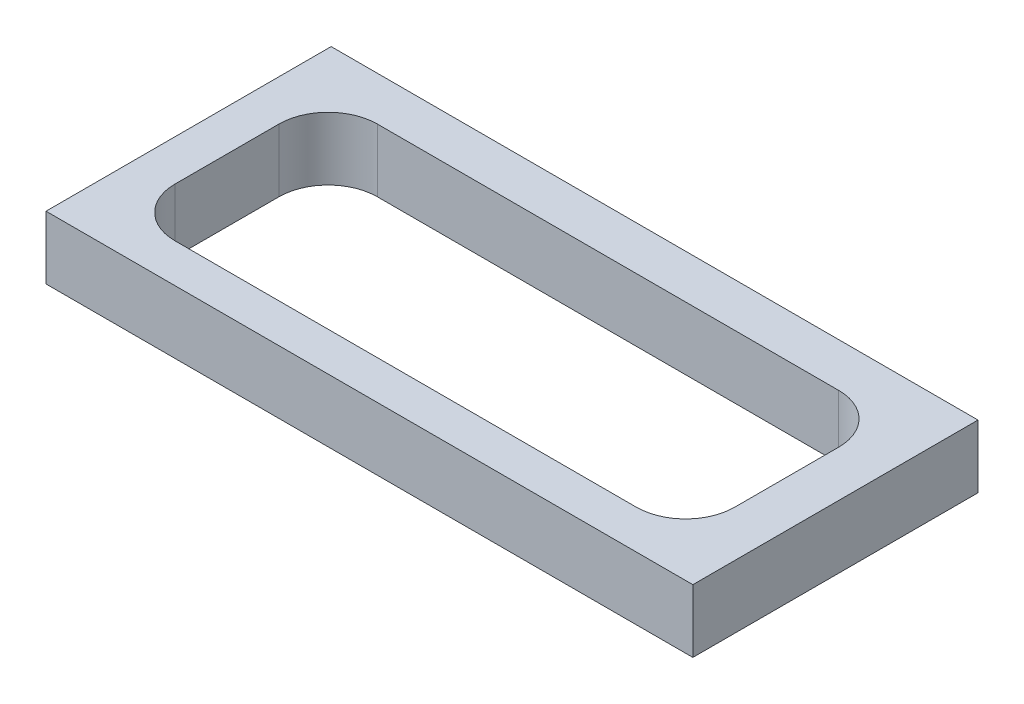
SolidWorks part; units mm, degrees
ref_plane "Front Plane" through (0, 0, 0) normal (0, 0, 1) x (1, 0, 0)
ref_plane "Top Plane" through (0, 0, 0) normal (0, 1, 0) x (1, 0, 0)
ref_plane "Right Plane" through (0, 0, 0) normal (1, 0, 0) x (0, 0, -1)
sketch "Sketch1" plane through (0, 0, 0) normal (0, 1, 0) x (1, 0, 0)
  line L1 (3.9, 0) -> (40.5, 0)
  line L2 (0, -3.9) -> (0, -12.15)
  line L3 (3.9, -16.05) -> (40.5, -16.05)
  line L4 (44.4, -3.9) -> (44.4, -12.15)
  line L9 (-3.2509, 3.4884) -> (48.0616, 3.4884)
  line L10 (-3.2509, 3.4884) -> (-3.2509, -19.1313)
  line L11 (-3.2509, -19.1313) -> (48.0616, -19.1313)
  line L12 (48.0616, 3.4884) -> (48.0616, -19.1313)
  arc A0 (40.5, 0) -> (44.4, -3.9) centre (40.5, -3.9) cw
  arc A1 (40.5, -16.05) -> (44.4, -12.15) centre (40.5, -12.15) ccw
  arc A2 (0, -12.15) -> (3.9, -16.05) centre (3.9, -12.15) ccw
  arc A3 (3.9, 0) -> (0, -3.9) centre (3.9, -3.9) ccw
  point P7 (44.4, 0)
  point P12 (0, -16.05)
  point P15 (0, 0)
  point P16 (48.0616, -19.1313)
  point P35 (84.0556, -35.8975)
  dimension "D3" = 3.9
  dimension "D1" = 44.4
  dimension "D2" = 16.05
extrude "Boss-Extrude1" add sketch "Sketch1" along normal blind 5
